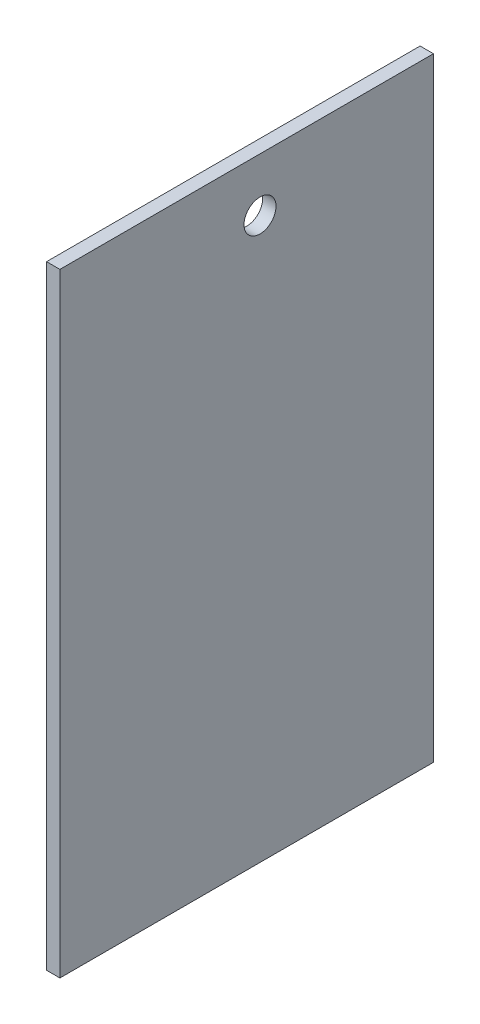
SolidWorks part; units mm, degrees
ref_plane "Front Plane" through (0, 0, 0) normal (0, 0, 1) x (1, 0, 0)
ref_plane "Top Plane" through (0, 0, 0) normal (0, 1, 0) x (1, 0, 0)
ref_plane "Right Plane" through (0, 0, 0) normal (1, 0, 0) x (0, 0, -1)
sketch "Sketch1" plane through (0, 0, 0) normal (1, 0, 0) x (0, 0, -1)
  line L1 (-44.45, 73.025) -> (44.45, 73.025)
  line L2 (-44.45, 73.025) -> (-44.45, -73.025)
  line L3 (-44.45, -73.025) -> (44.45, -73.025)
  line L4 (44.45, 73.025) -> (44.45, -73.025)
  line L5 (-44.45, 73.025) -> (44.45, -73.025) construction
  line L6 (-44.45, -73.025) -> (44.45, 73.025) construction
  point P0 (0, 0)
  dimension "D1" = 146.05
  dimension "D2" = 88.9
extrude "Boss-Extrude1" add sketch "Sketch1" along normal blind 3.175
sketch "Sketch2" plane through (3.175, 0, 0) normal (1, 0, 0) x (0, 0, -1)
  line L0 (-44.45, -73.025) -> (44.45, -73.025) construction
  line L1 (-44.45, 73.025) -> (-44.45, -73.025) construction
  circle A0 centre (3.175, 60.325) radius 3.81
  dimension "D3" = 7.62
  dimension "D1" = 133.35
  dimension "D2" = 47.625
extrude "Cut-Extrude1" cut sketch "Sketch2" against normal through all
